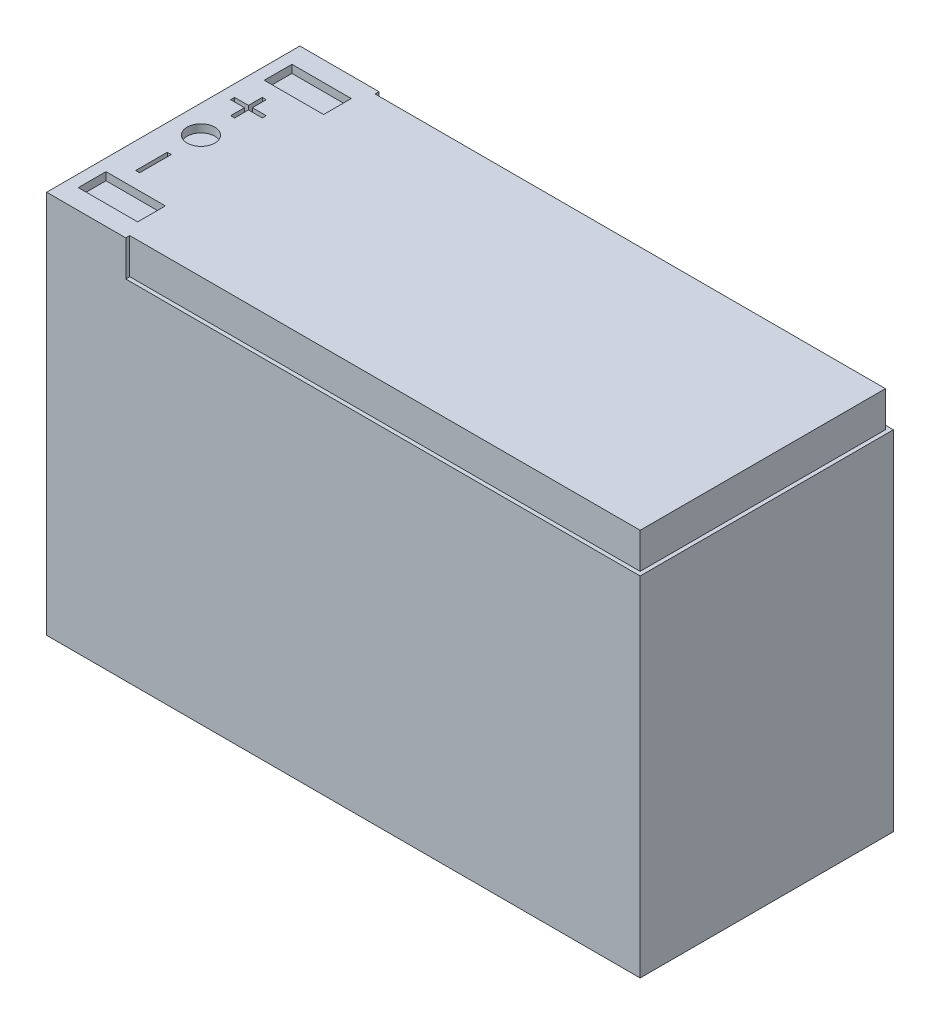
SolidWorks part; units mm, degrees
ref_plane "Front Plane" through (0, 0, 0) normal (0, 0, 1) x (1, 0, 0)
ref_plane "Top Plane" through (0, 0, 0) normal (0, 1, 0) x (1, 0, 0)
ref_plane "Right Plane" through (0, 0, 0) normal (1, 0, 0) x (0, 0, -1)
sketch "Sketch1" plane through (0, 0, 0) normal (0, 0, 1) x (1, 0, 0)
  line L1 (0, 0) -> (150, 0)
  line L2 (0, 0) -> (0, -97)
  line L3 (0, -97) -> (150, -97)
  line L4 (150, 0) -> (150, -97)
  dimension "D1" = 97
  dimension "D2" = 150
extrude "Boss-Extrude2" add sketch "Sketch1" along normal blind 64
sketch "Sketch3" plane through (0, 0, 0) normal (0, 1, 0) x (1, 0, 0)
  line L0 (20, 0) -> (20, -1)
  line L1 (150, 0) -> (0, 0) construction
  line L2 (20, -1) -> (149, -1)
  line L3 (149, -1) -> (149, -63)
  line L4 (149, -63) -> (20, -63)
  line L5 (20, -63) -> (20, -64)
  line L6 (150, -64) -> (0, -64) construction
  line L7 (0, -64) -> (0, 0) construction
  line L8 (150, -64) -> (150, 0) construction
  dimension "D1" = 20
  dimension "D2" = 1
  dimension "D3" = 1
  dimension "D4" = 1
extrude "Cut-Extrude1" cut sketch "Sketch3" against normal blind 9 and the other way through all
sketch "Sketch4" plane through (0, 0, 0) normal (0, 1, 0) x (1, 0, 0)
  line L0 (0, -32) -> (149, -32) construction
  line L1 (3, -5) -> (18, -5)
  line L2 (3, -5) -> (3, -12)
  line L3 (3, -12) -> (18, -12)
  line L4 (18, -5) -> (18, -12)
  line L5 (0, -64) -> (0, 0) construction
  line L6 (149, -63) -> (149, -1) construction
  line L7 (20, 0) -> (0, 0) construction
  line L8 (18, -59) -> (18, -52)
  line L9 (3, -52) -> (18, -52)
  line L10 (3, -59) -> (3, -52)
  line L11 (3, -59) -> (18, -59)
  line L12 (6.5, -16) -> (6.5, -19.5)
  line L13 (6.5, -19.5) -> (3, -19.5)
  line L14 (3, -19.5) -> (3, -20.5)
  line L15 (3, -20.5) -> (6.5, -20.5)
  line L16 (6.5, -20.5) -> (6.5, -24)
  line L17 (6.5, -24) -> (7.5, -24)
  line L18 (7.5, -24) -> (7.5, -20.5)
  line L19 (7.5, -20.5) -> (11, -20.5)
  line L20 (11, -20.5) -> (11, -19.5)
  line L21 (11, -19.5) -> (7.5, -19.5)
  line L22 (7.5, -19.5) -> (7.5, -16)
  line L23 (7.5, -16) -> (6.5, -16)
  line L24 (6.5, -40) -> (6.5, -48)
  line L25 (6.5, -48) -> (7.5, -48)
  line L26 (7.5, -48) -> (7.5, -40)
  line L27 (7.5, -40) -> (6.5, -40)
  circle A0 centre (7, -32) radius 3.5
  point P30 (7, -16)
  dimension "D5" = 7
  dimension "D1" = 5
  dimension "D2" = 3
  dimension "D3" = 15
  dimension "D4" = 7
  dimension "D6" = 3.5
  dimension "D7" = 1
  dimension "D8" = 3.5
  dimension "D9" = 1
  dimension "D10" = 1
  dimension "D11" = 3.5
  dimension "D12" = 3.5
  dimension "D13" = 1
  dimension "D14" = 3.5
  dimension "D15" = 3
  dimension "D16" = 4
  dimension "D17" = 1
  dimension "D18" = 8
  dimension "D19" = 4
  dimension "D20" = 7
extrude "Cut-Extrude2" cut sketch "Sketch4" against normal blind 2
